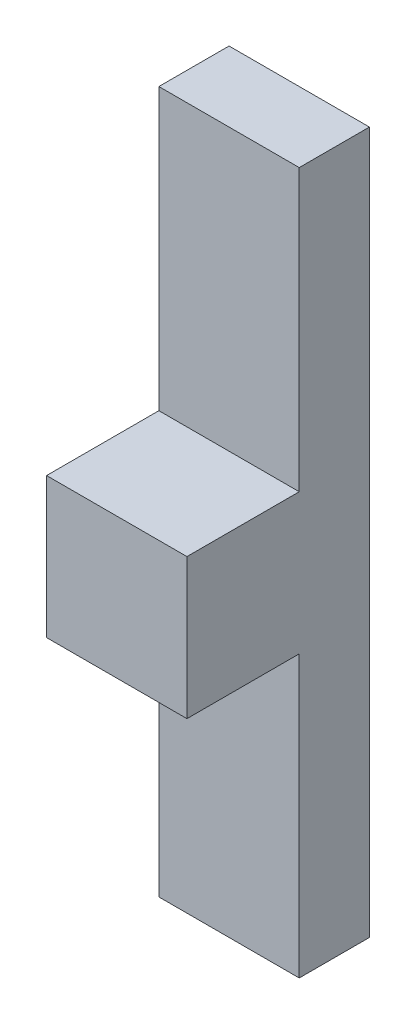
SolidWorks part; units mm, degrees
ref_plane "Front Plane" through (0, 0, 0) normal (0, 0, 1) x (1, 0, 0)
ref_plane "Top Plane" through (0, 0, 0) normal (0, 1, 0) x (1, 0, 0)
ref_plane "Right Plane" through (0, 0, 0) normal (1, 0, 0) x (0, 0, -1)
sketch "Sketch1" plane through (0, 0, 0) normal (0, 0, 1) x (1, 0, 0)
  line L0 (15.4312, -31.75) -> (-41.91, -31.75) construction
  line L1 (-15.6192, 31.75) -> (-2.9192, 31.75)
  line L2 (-15.6192, 31.75) -> (-15.6192, -31.75)
  line L3 (-15.6192, -31.75) -> (-2.9192, -31.75)
  line L4 (-2.9192, 31.75) -> (-2.9192, -31.75)
  line L5 (-15.6192, 31.75) -> (-2.9192, -31.75) construction
  line L6 (-15.6192, -31.75) -> (-2.9192, 31.75) construction
  point P0 (-9.2692, 0)
  point P8 (-7.9482, 0)
  point P9 (-7.1188, 0)
  point P10 (0, 0)
  point P11 (0, 0)
  point P13 (-7.9482, 0)
  point P14 (-7.9482, 0)
  point P16 (-9.2692, 0)
  dimension "D1" = 12.7
extrude "Boss-Extrude1" add sketch "Sketch1" along normal blind 6.35
sketch "Sketch2" plane through (0, 0, 6.35) normal (0, 0, 1) x (1, 0, 0)
  line L0 (-15.6192, 31.75) -> (-15.6192, -31.75) construction
  line L1 (-2.9192, -6.35) -> (-15.6192, -6.35)
  line L2 (-2.9192, -6.35) -> (-2.9192, 6.35)
  line L3 (-2.9192, 6.35) -> (-15.6192, 6.35)
  line L4 (-15.6192, -6.35) -> (-15.6192, 6.35)
  line L5 (-2.9192, -6.35) -> (-15.6192, 6.35) construction
  line L6 (-2.9192, 6.35) -> (-15.6192, -6.35) construction
  line L7 (-2.9192, -31.75) -> (-2.9192, 31.75) construction
  point P0 (-9.2692, 0)
  dimension "D1" = 12.7
extrude "Boss-Extrude2" add sketch "Sketch2" along normal blind 10.16
